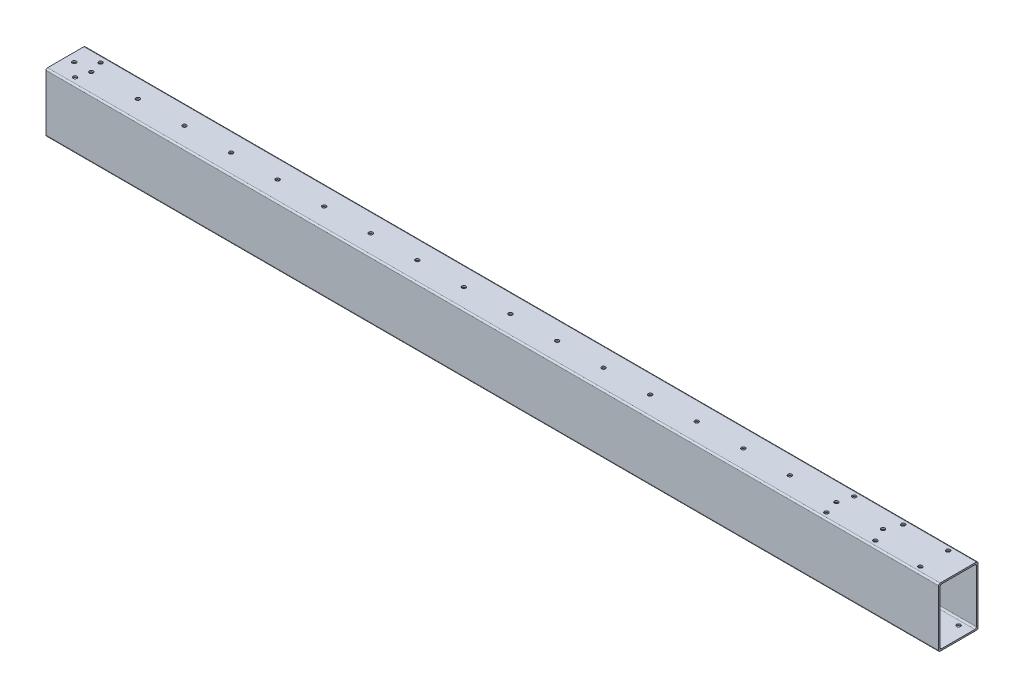
SolidWorks part; units mm, degrees
material "A500"
ref_plane "Alzado" through (0, 0, 0) normal (0, 0, 1) x (1, 0, 0)
ref_plane "Planta" through (0, 0, 0) normal (0, 1, 0) x (1, 0, 0)
ref_plane "Vista lateral" through (0, 0, 0) normal (1, 0, 0) x (0, 0, -1)
sketch "Sketch1" plane through (0, 0, 0) normal (1, 0, 0) x (0, 0, -1)
  line L1 (25.4, 38.1) -> (-25.4, 38.1)
  line L2 (25.4, 38.1) -> (25.4, -38.1)
  line L3 (25.4, -38.1) -> (-25.4, -38.1)
  line L4 (-25.4, 38.1) -> (-25.4, -38.1)
  line L5 (25.4, 38.1) -> (-25.4, -38.1) construction
  line L6 (25.4, -38.1) -> (-25.4, 38.1) construction
  point P0 (0, 0)
  dimension "D1" = 76.2
  dimension "D2" = 50.8
extrude "Boss-Extrude1" add sketch "Sketch1" against normal blind 1150
sketch "Sketch2" plane through (0, 0, 0) normal (1, 0, 0) x (0, 0, -1)
  line L0 (25.4, 38.1) -> (-25.4, 38.1) construction
  line L1 (23.4, 36.1) -> (-23.4, 36.1)
  line L2 (23.4, 36.1) -> (23.4, -36.1)
  line L3 (23.4, -36.1) -> (-23.4, -36.1)
  line L4 (-23.4, 36.1) -> (-23.4, -36.1)
  line L5 (23.4, 36.1) -> (-23.4, -36.1) construction
  line L6 (23.4, -36.1) -> (-23.4, 36.1) construction
  line L7 (25.4, -38.1) -> (25.4, 38.1) construction
  point P0 (0, 0)
  dimension "D1" = 2
  dimension "D2" = 2
extrude "Cut-Extrude1" cut sketch "Sketch2" against normal through all
fillet "Fillet2" radius 2 8 edges at (-575, -38.1, -25.4) (-575, -38.1, 25.4) (-575, 38.1, 25.4) (-575, 38.1, -25.4) (-575, -36.1, -23.4) (-575, 36.1, -23.4) (-575, -36.1, 23.4) (-575, 36.1, 23.4)
sketch "Croquis1" plane through (0, -38.1, 0) normal (0, -1, 0) x (1, 0, 0)
  line L0 (-76.2, 25.4) -> (-76.2, -25.4) construction
  line L1 (-1150, 25.4) -> (0, 25.4) construction
  line L2 (0, -25.4) -> (-1150, -25.4) construction
  line L3 (0, 23.4) -> (0, -23.4) construction
  line L4 (0, 15.4) -> (-76.2, 15.4) construction
  line L5 (0, -15.4) -> (-76.2, -15.4) construction
  line L6 (-76.2, 0) -> (0, 0) construction
  circle A0 centre (-38.1, 0) radius 2.5
  circle A1 centre (-61.2, 15.4) radius 2.5
  circle A2 centre (-15, 15.4) radius 2.5
  circle A3 centre (-15, -15.4) radius 2.5
  circle A4 centre (-61.2, -15.4) radius 2.5
  dimension "D8" = 5
  dimension "D9" = 5
  dimension "D10" = 5
  dimension "D11" = 5
  dimension "D12" = 5
  dimension "D1" = 76.2
  dimension "D2" = 10
  dimension "D3" = 10
  dimension "D4" = 15
  dimension "D5" = 15
  dimension "D6" = 15
  dimension "D7" = 15
extrude "Cortar-Extruir1" cut sketch "Croquis1" against normal blind 5
pattern_linear "MatrizL1" count 4 spacing 357.9333 along (-1, 0, 0) of "Cortar-Extruir1"
sketch "Croquis2" plane through (0, 0, -25.4) normal (0, 0, -1) x (-1, 0, 0)
  line L0 (0, 8.1) -> (1150, 8.1) construction
  line L1 (0, -36.1) -> (0, 36.1) construction
  line L2 (1150, -36.1) -> (1150, 36.1) construction
  line L3 (0, 38.1) -> (1150, 38.1) construction
  line L4 (0, -18.1) -> (1150, -18.1) construction
  line L5 (1150, -38.1) -> (0, -38.1) construction
  circle A0 centre (1100, 8.1) radius 2.5
  circle A1 centre (225, 8.1) radius 2.5
  circle A2 centre (75, -18.1) radius 2.5
  circle A3 centre (325, -18.1) radius 2.5
  circle A4 centre (675, -18.1) radius 2.5
  circle A5 centre (1025, -18.1) radius 2.5
  dimension "D4" = 5
  dimension "D5" = 5
  dimension "D13" = 5
  dimension "D14" = 5
  dimension "D15" = 5
  dimension "D16" = 5
  dimension "D1" = 30
  dimension "D2" = 50
  dimension "D3" = 225
  dimension "D6" = 20
  dimension "D7" = 75
  dimension "D8" = 250
  dimension "D9" = 350
  dimension "D10" = 350
extrude "Cortar-Extruir2" cut sketch "Croquis2" against normal blind 10
sketch "Croquis3" plane through (0, 38.1, 0) normal (0, 1, 0) x (1, 0, 0)
  line L0 (0, 17.9) -> (-152, 17.9) construction
  line L1 (0, 23.4) -> (0, -23.4) construction
  line L2 (-152, 17.9) -> (-152, -17.9) construction
  line L3 (-152, -17.9) -> (0, -17.9) construction
  line L4 (-1150, 25.4) -> (0, 25.4) construction
  line L5 (0, -25.4) -> (-1150, -25.4) construction
  circle A0 centre (-31, 17.9) radius 2.5
  circle A1 centre (-89, 17.9) radius 2.5
  circle A2 centre (-152, 17.9) radius 2.5
  circle A3 centre (-152, -17.9) radius 2.5
  circle A4 centre (-89, -17.9) radius 2.5
  circle A5 centre (-31, -17.9) radius 2.5
  dimension "D8" = 5
  dimension "D9" = 5
  dimension "D10" = 5
  dimension "D11" = 5
  dimension "D12" = 5
  dimension "D13" = 5
  dimension "D1" = 7.5
  dimension "D2" = 7.5
  dimension "D3" = 31
  dimension "D4" = 31
  dimension "D5" = 58
  dimension "D6" = 58
  dimension "D7" = 152
extrude "Cortar-Extruir3" cut sketch "Croquis3" against normal blind 10
sketch "Croquis4" plane through (0, 38.1, 0) normal (0, 1, 0) x (1, 0, 0)
  line L0 (-1150, 0) -> (-1107.8204, 0) construction
  line L1 (-1150, 23.4) -> (-1150, -23.4) construction
  circle A0 centre (-1117, 0) radius 2.5
  dimension "D2" = 5
  dimension "D1" = 33
extrude "Cortar-Extruir4" cut sketch "Croquis4" against normal blind 10
pattern_linear "MatrizL2" count 18 spacing 60 along (1, 0, 0) of "Cortar-Extruir4"
sketch "Croquis5" plane through (0, 38.1, 0) normal (0, 1, 0) x (1, 0, 0)
  line L0 (-1121.5, 25.4) -> (-1121.5, -25.4) construction
  line L1 (-1150, 25.4) -> (0, 25.4) construction
  line L2 (0, -25.4) -> (-1150, -25.4) construction
  line L3 (-1150, 23.4) -> (-1150, -23.4) construction
  line L4 (-1121.5, 0) -> (-1150, 0) construction
  circle A0 centre (-1121.5, 16.4) radius 2.5
  circle A1 centre (-1121.5, -16.4) radius 2.5
  circle A2 centre (-1139, 0) radius 2.5
  dimension "D4" = 5
  dimension "D5" = 5
  dimension "D6" = 5
  dimension "D1" = 28.5
  dimension "D2" = 16.4
  dimension "D3" = 16.4
  dimension "D7" = 11
extrude "Cortar-Extruir5" cut sketch "Croquis5" against normal blind 10
